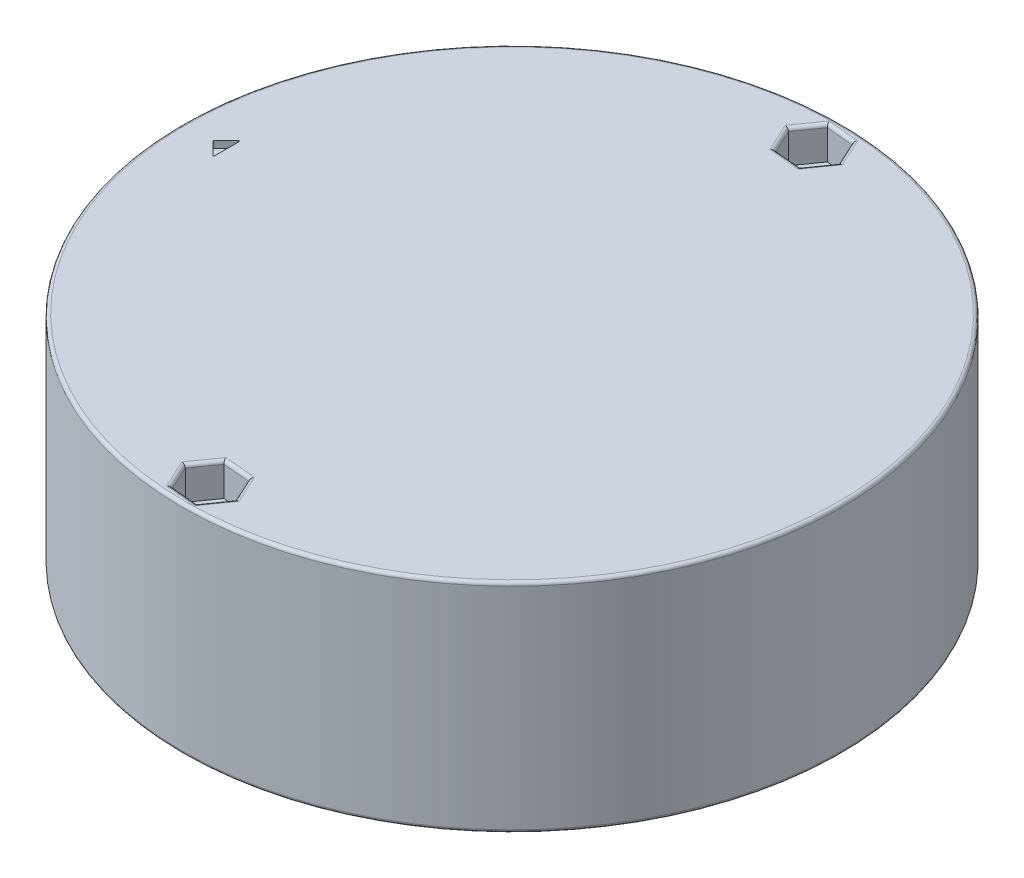
SolidWorks part; units mm, degrees
ref_plane "Front Plane" through (0, 0, 0) normal (0, 0, 1) x (1, 0, 0)
ref_plane "Top Plane" through (0, 0, 0) normal (0, 1, 0) x (1, 0, 0)
ref_plane "Right Plane" through (0, 0, 0) normal (1, 0, 0) x (0, 0, -1)
sketch "Sketch1" plane through (0, 0, 0) normal (0, 1, 0) x (1, 0, 0)
  circle A2 centre (0, 0) radius 50
  circle A7 centre (0.7744, 44.9933) radius 2
  circle A8 centre (-0.7744, -44.9933) radius 2.1
  dimension "D3" = 4.2
  dimension "D1" = 100
  dimension "D2" = 4
extrude "Boss-Extrude1" add sketch "Sketch1" along normal blind 5
sketch "Sketch10" plane through (0, 0, 0) normal (0, -1, 0) x (1, 0, 0)
  line L0 (-2.8757, 41.3537) -> (-1.3256, -41.356) construction
  line L7 (3.4283, 44.9933) -> (1.327, 48.633)
  line L8 (1.327, 48.633) -> (-2.8757, 48.633)
  line L9 (-2.8757, 48.633) -> (-4.9771, 44.9933)
  line L10 (-4.9771, 44.9933) -> (-2.8757, 41.3537)
  line L11 (-2.8757, 41.3537) -> (1.327, 41.3537)
  line L12 (1.327, 41.3537) -> (3.4283, 44.9933)
  line L13 (4.9744, -44.9933) -> (2.8744, -41.356)
  line L14 (2.8744, -41.356) -> (-1.3256, -41.356)
  line L15 (-1.3256, -41.356) -> (-3.4256, -44.9933)
  line L16 (-3.4256, -44.9933) -> (-1.3256, -48.6306)
  line L17 (-1.3256, -48.6306) -> (2.8744, -48.6306)
  line L18 (2.8744, -48.6306) -> (4.9744, -44.9933)
  line L19 (1.327, 41.3537) -> (2.8771, -41.3608) construction
  circle A0 centre (-0.7744, 44.9933) radius 3.6396 construction
  circle A1 centre (0.7744, -44.9933) radius 3.6373 construction
  dimension "D1" = 4.2027
  dimension "D2" = 4.2
extrude "Cut-Extrude2" cut sketch "Sketch10" against normal blind 4
sketch "Sketch13" plane through (0, 5, 0) normal (0, 1, 0) x (1, 0, 0)
  circle A0 centre (0, 0) radius 50 construction
  circle A1 centre (0, 0) radius 50
  arc A5 (-4.1582, 45.8117) -> (-5.7322, -45.6415) centre (0, 0) ccw
  circle A8 centre (0, 0) radius 46 construction
  arc A9 (4.1582, -45.8117) -> (5.7322, 45.6415) centre (0, 0) ccw
  arc A10 (-4.1582, 45.8117) -> (5.7322, 45.6415) centre (0.7744, 44.9933) ccw
  arc A11 (4.1582, -45.8117) -> (-5.7322, -45.6415) centre (-0.7744, -44.9933) ccw
  point P5 (0, 0)
  dimension "D2" = 10
  dimension "D3" = 10
  dimension "D1" = 46
extrude "Boss-Extrude2" add sketch "Sketch13" along normal blind 23
sketch "Sketch14" plane through (0, 28, 0) normal (0, 1, 0) x (1, 0, 0)
  circle A0 centre (0, 0) radius 50
extrude "Boss-Extrude3" add sketch "Sketch14" along normal blind 5
sketch "Sketch12" plane through (0, 33, -10) normal (0, -1, 0) x (-1, 0, 0)
  line L7 (3.4111, 35.373) -> (0.9896, 38.8079)
  line L8 (0.9896, 38.8079) -> (-3.1959, 38.4282)
  line L9 (-3.1959, 38.4282) -> (-4.9599, 34.6136)
  line L10 (-4.9599, 34.6136) -> (-2.5383, 31.1787)
  line L11 (-2.5383, 31.1787) -> (1.6472, 31.5584)
  line L12 (1.6472, 31.5584) -> (3.4111, 35.373)
  line L13 (4.9572, -54.6139) -> (2.5372, -51.1812)
  line L14 (2.5372, -51.1812) -> (-1.6456, -51.5606)
  line L15 (-1.6456, -51.5606) -> (-3.4084, -55.3728)
  line L16 (-3.4084, -55.3728) -> (-0.9884, -58.8055)
  line L17 (-0.9884, -58.8055) -> (3.1944, -58.426)
  line L18 (3.1944, -58.426) -> (4.9572, -54.6139)
  circle A0 centre (-0.7744, 34.9933) radius 3.6396 construction
  circle A1 centre (0.7744, -54.9933) radius 3.6373 construction
  dimension "D1" = 4.2027
  dimension "D2" = 4.2
extrude "Cut-Extrude5" cut sketch "Sketch12" along normal blind 5
sketch "Sketch15" plane through (0, 0, 0) normal (0, -1, 0) x (1, 0, 0)
  circle A0 centre (0, 0) radius 37.5
  dimension "D1" = 75
extrude "Cut-Extrude6" cut sketch "Sketch15" against normal blind 10
fillet "Fillet1" radius 4 4 edges at (5.7322, 16.5, -45.6415) (-4.1582, 16.5, -45.8117) (-5.7322, 16.5, 45.6415) (4.1582, 16.5, 45.8117)
fillet "Fillet2" radius 0.5 2 edges at (0, 5, 37.5) (0, 0, -37.5)
fillet "Fillet3" radius 0.5 2 edges at (0, 33, 50) (0, 0, 50)
fillet "Fillet4" radius 0.3 2 edges at (-0.7744, 28, 42.8933) (0.7744, 28, -46.9933)
fillet "Fillet5" radius 0.5 12 edges at (3.7491, 33, -42.8962) (4.0779, 33, -46.5209) (1.1032, 33, -48.6181) (-2.2003, 33, -47.0905) (-2.5292, 33, -43.4657) (0.4456, 33, -41.3686) (2.1984, 33, 47.0891) (2.527, 33, 43.4667) (-0.4458, 33, 41.3709) (-3.7472, 33, 42.8975) (-4.0758, 33, 46.52) (-1.103, 33, 48.6158)
fillet "Fillet6" radius 0.3 12 edges at (0.7744, 0, -41.356) (-2.3756, 0, -43.1747) (-2.3756, 0, -46.812) (0.7744, 0, -48.6306) (3.9244, 0, -46.812) (3.9244, 0, -43.1747) (-0.7744, 0, 48.633) (-3.9264, 0, 46.8132) (-3.9264, 0, 43.1735) (-0.7744, 0, 41.3537) (2.3776, 0, 43.1735) (2.3776, 0, 46.8132)
fillet "Fillet7" radius 1 16 edges at (-5.5766, 28, -44.8694) (0.6883, 28, -39.9941) (7.1174, 28, -44.6509) (45.9932, 28, 0.7916) (5.5766, 28, 44.8694) (-0.6883, 28, 39.9941) (-7.1174, 28, 44.6509) (-45.9932, 28, -0.7916) (5.5766, 5, 44.8694) (-0.6883, 5, 39.9941) (-7.1174, 5, 44.6509) (-45.9932, 5, -0.7916) (-5.5766, 5, -44.8694) (0.6883, 5, -39.9941) (7.1174, 5, -44.6509) (45.9932, 5, 0.7916)
sketch "Sketch16" plane through (0, 33, 0) normal (0, 1, 0) x (1, 0, 0)
  line L0 (0, 0) -> (6.3025, 0) construction
  line L1 (-45.3158, -0.0707) -> (-43.4359, -1.9506)
  line L2 (-43.2652, -1.8799) -> (-43.2652, 1.8799)
  line L3 (-43.4359, 1.9506) -> (-45.3158, 0.0707)
  arc A0 (-43.4359, -1.9506) -> (-43.2652, -1.8799) centre (-43.3652, -1.8799) ccw
  arc A1 (-43.2652, 1.8799) -> (-43.4359, 1.9506) centre (-43.3652, 1.8799) ccw
  arc A2 (-45.3158, -0.0707) -> (-45.3158, 0.0707) centre (-45.2451, 0) cw
  point P7 (-43.2652, -2.1213)
  point P10 (-43.2652, 2.1213)
  point P13 (-45.3865, 0)
  dimension "D3" = 0.1
  dimension "D1" = 3
  dimension "D2" = 3
extrude "Cut-Extrude7" cut sketch "Sketch16" against normal blind 1
